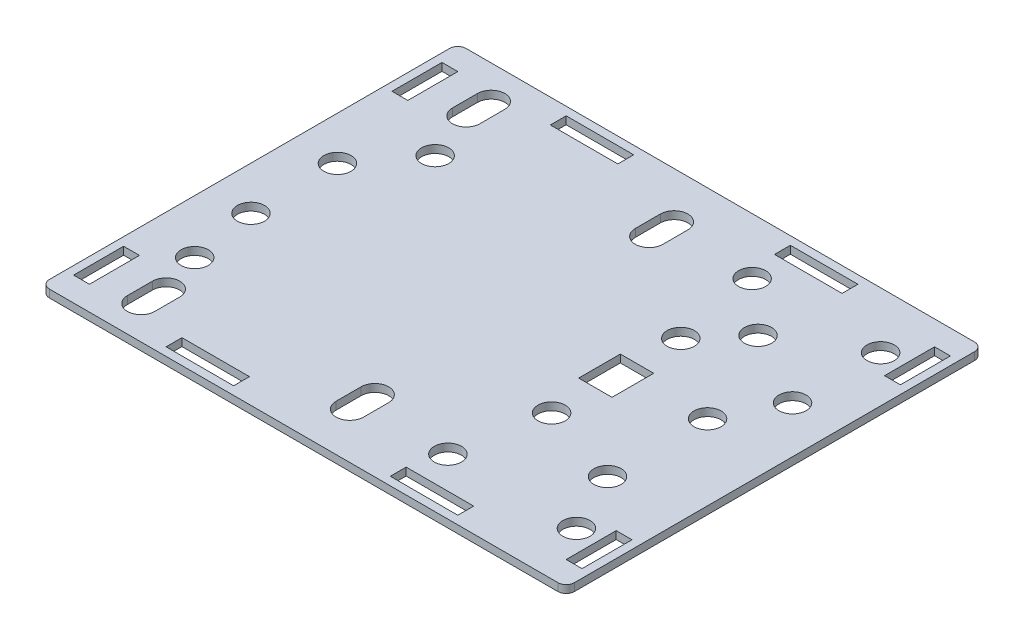
SolidWorks part; units mm, degrees
material "PE High Density Film"
ref_plane "Front Plane" through (0, 0, 0) normal (0, 0, 1) x (1, 0, 0)
ref_plane "Top Plane" through (0, 0, 0) normal (0, 1, 0) x (1, 0, 0)
ref_plane "Right Plane" through (0, 0, 0) normal (1, 0, 0) x (0, 0, -1)
sketch "Sketch1" plane through (0, 0, 0) normal (0, 1, 0) x (1, 0, 0)
  line L1 (-76.2, 63.5) -> (76.2, 63.5)
  line L2 (-76.2, 63.5) -> (-76.2, -63.5)
  line L3 (-76.2, -63.5) -> (76.2, -63.5)
  line L4 (76.2, 63.5) -> (76.2, -63.5)
  line L5 (-76.2, 63.5) -> (76.2, -63.5) construction
  line L6 (-76.2, -63.5) -> (76.2, 63.5) construction
  point P0 (0, 0)
  dimension "D1" = 127
  dimension "D2" = 152.4
extrude "Boss-Extrude1" add sketch "Sketch1" along normal blind 2.3622
sketch "Sketch9" plane through (0, 0, 0) normal (0, -1, 0) x (1, 0, 0)
  circle A0 centre (60.8584, 27.94) radius 4.15
  circle A1 centre (60.8584, -2.54) radius 4.15
  dimension "D1" = 8.3
  dimension "D2" = 8.3
extrude "Cut-Extrude8" cut sketch "Sketch9" against normal through all
sketch "Sketch16" plane through (0, 0, 0) normal (0, -1, 0) x (-1, 0, 0)
  circle A0 centre (-69.5999, 19.7043) radius 4.15
  circle A1 centre (-46.5226, 32.2642) radius 4.15
  dimension "D1" = 8.3
extrude "Cut-Extrude14" cut sketch "Sketch16" against normal through all
sketch "Sketch26" plane through (0, 2.3622, 0) normal (0, 1, 0) x (1, 0, 0)
  line L1 (40.64, 6.35) -> (30.48, 6.35)
  line L2 (40.64, 6.35) -> (40.64, -6.35)
  line L3 (40.64, -6.35) -> (30.48, -6.35)
  line L4 (30.48, 6.35) -> (30.48, -6.35)
extrude "Cut-Extrude26" cut sketch "Sketch26" against normal through all
sketch "Sketch27" plane through (0, 0, 0) normal (0, -1, 0) x (1, 0, 0)
  circle A0 centre (-59.8314, 33.0604) radius 4.15
  circle A1 centre (-50.0917, -30.48) radius 4.15
  dimension "D1" = 8.3
extrude "Cut-Extrude27" cut sketch "Sketch27" against normal through all
sketch "Sketch29" plane through (0, 2.3622, 0) normal (0, 1, 0) x (1, 0, 0)
  circle A0 centre (35.56, 19.6812) radius 4.15
  circle A1 centre (35.56, -19.6812) radius 4.15
  dimension "D1" = 8.3
extrude "Cut-Extrude28" cut sketch "Sketch29" against normal through all
sketch "Sketch30" plane through (0, 2.3622, 0) normal (0, 1, 0) x (1, 0, 0)
  line L0 (75.66, -63.5) -> (-73.66, -63.5) construction
  line L2 (-76.2, -63.5) -> (76.2, -63.5) construction
  circle A0 centre (69.8033, -46.355) radius 4.15
  circle A1 centre (30.6352, -46.355) radius 4.15
  dimension "D1" = 8.3
  dimension "D2" = 17.145
  dimension "D3" = 17.145
extrude "Cut-Extrude29" cut sketch "Sketch30" against normal through all
mirror "Mirror8" about plane through (0, 0, 0) normal (0, 0, 1) of "Cut-Extrude29"
sketch "Sketch31" plane through (0, 2.3622, 0) normal (0, 1, 0) x (1, 0, 0)
  circle A0 centre (-62.9423, -12.7955) radius 4.15
  circle A1 centre (-62.9423, 13.5496) radius 4.15
  dimension "D1" = 8.3
extrude "Cut-Extrude30" cut sketch "Sketch31" against normal through all
sketch "Sketch32" plane through (0, 2.3622, 0) normal (0, 1, 0) x (1, 0, 0)
  line L0 (76.2, -46.4055) -> (73.953, -46.4055) construction
  line L1 (76.2, -63.5) -> (76.2, 63.5) construction
  circle A0 centre (69.8033, -46.355) radius 4.15 construction
sketch "Sketch34" plane through (76.2, 0, 0) normal (1, 0, 0) x (0, 0, -1)
  line L1 (-63.5, 2.3622) -> (63.5, 2.3622)
  line L2 (-63.5, 2.3622) -> (-63.5, 0)
  line L3 (-63.5, 0) -> (63.5, 0)
  line L4 (63.5, 2.3622) -> (63.5, 0)
extrude "Boss-Extrude2" add sketch "Sketch34" along normal blind 7.62
sketch "Sketch36" plane through (0, 2.3622, 0) normal (0, 1, 0) x (1, 0, 0)
  line L0 (3.81, 63.5) -> (3.81, -76.7285) construction
  line L1 (83.82, 63.5) -> (-76.2, 63.5) construction
sketch "Sketch37" plane through (0, 0, 0) normal (0, -1, 0) x (-1, 0, 0)
  line L0 (-3.81, -63.5) -> (-3.81, 68.2955) construction
  line L1 (76.2, -63.5) -> (-83.82, -63.5) construction
ref_plane "Plane1" through (3.81, 0, 0) normal (1, 0, 0) x (0, 0, -1)
sketch "Sketch38" plane through (0, 2.3622, 0) normal (0, 1, 0) x (1, 0, 0)
  line L0 (3.81, 63.5) -> (3.81, -76.7285) construction
  line L1 (48.26, -60.96) -> (-40.64, -60.96)
  line L2 (48.26, -60.96) -> (48.26, -56.134)
  line L3 (48.26, -56.134) -> (-40.64, -56.134)
  line L4 (-40.64, -60.96) -> (-40.64, -56.134)
  line L5 (48.26, -60.96) -> (-40.64, -56.134) construction
  line L6 (48.26, -56.134) -> (-40.64, -60.96) construction
  line L7 (-76.2, -63.5) -> (83.82, -63.5) construction
  point P0 (3.81, -58.547)
  dimension "D1" = 2.54
  dimension "D2" = 4.826
  dimension "D3" = 88.9
extrude "Cut-Extrude34" cut sketch "Sketch38" against normal blind 7.62
mirror "Mirror13" about plane through (0, 0, 0) normal (0, 0, 1) of "Cut-Extrude34"
sketch "Sketch39" plane through (0, 2.3622, 0) normal (0, 1, 0) x (1, 0, 0)
  line L0 (83.82, 63.5) -> (83.82, -63.5) construction
  line L1 (81.28, -56.134) -> (76.454, -56.134)
  line L2 (81.28, -56.134) -> (81.28, -40.894)
  line L3 (81.28, -40.894) -> (76.454, -40.894)
  line L4 (76.454, -56.134) -> (76.454, -40.894)
  line L5 (81.28, -56.134) -> (76.454, -40.894) construction
  line L6 (81.28, -40.894) -> (76.454, -56.134) construction
  line L7 (48.26, -56.134) -> (-40.64, -56.134) construction
  point P0 (78.867, -48.514)
  dimension "D1" = 4.826
  dimension "D2" = 2.54
  dimension "D3" = 15.24
  dimension "D4" = 0
extrude "Cut-Extrude35" cut sketch "Sketch39" against normal blind 7.62
mirror "Mirror14" about plane through (0, 0, 0) normal (0, 0, 1) of "Cut-Extrude35"
mirror "Mirror15" about plane through (3.81, 0, 0) normal (1, 0, 0) of "Mirror14", "Cut-Extrude35"
sketch "Sketch13" plane through (0, 0, 0) normal (0, -1, 0) x (-1, 0, 0)
  line L0 (55.88, -45.72) -> (55.88, -53.34) construction
  line L1 (60.0529, -45.72) -> (60.0529, -53.34)
  line L2 (51.7071, -45.72) -> (51.7071, -53.34)
  line L3 (76.2, -63.5) -> (-83.82, -63.5) construction
  line L4 (76.2, 61.0698) -> (76.2, -60.8502) construction
  line L5 (-3.81, 49.403) -> (-3.81, 41.783) construction
  line L6 (0.381, 49.403) -> (0.381, 41.783)
  line L7 (-8.001, 49.403) -> (-8.001, 41.783)
  line L8 (-3.81, 63.5) -> (-3.81, -76.7285) construction
  line L10 (-48.26, 56.134) -> (40.64, 56.134) construction
  arc A0 (60.0529, -45.72) -> (51.7071, -45.72) centre (55.88, -45.72) ccw
  arc A1 (51.7071, -53.34) -> (60.0529, -53.34) centre (55.88, -53.34) ccw
  arc A2 (0.381, 49.403) -> (-8.001, 49.403) centre (-3.81, 49.403) ccw
  arc A3 (-8.001, 41.783) -> (0.381, 41.783) centre (-3.81, 41.783) ccw
  point P2 (55.88, -49.53)
  point P13 (-3.81, 45.593)
  point P28 (-3.81, 53.594)
  dimension "D5" = 2.54
  dimension "D1" = 7.62
  dimension "D2" = 10.16
  dimension "D3" = 20.32
  dimension "D4" = 7.62
  dimension "D6" = 8.382
extrude "Cut-Extrude12" cut sketch "Sketch13" against normal through all
mirror "Mirror16" about plane through (0, 0, 0) normal (0, 0, 1) of "Cut-Extrude12"
sketch "Sketch40" plane through (0, 0, 60.96) normal (0, 0, -1) x (-1, 0, 0)
  line L0 (40.64, 0) -> (-48.26, 0) construction
  line L1 (20.066, 0) -> (-27.686, 0)
  line L2 (20.066, 0) -> (20.066, 2.3622)
  line L3 (20.066, 2.3622) -> (-27.686, 2.3622)
  line L4 (-27.686, 0) -> (-27.686, 2.3622)
  line L5 (40.64, 2.3622) -> (-48.26, 2.3622) construction
  line L6 (40.64, 0) -> (40.64, 2.3622) construction
  line L7 (-48.26, 0) -> (-48.26, 2.3622) construction
  dimension "D1" = 20.574
  dimension "D2" = 20.574
extrude "Boss-Extrude3" add sketch "Sketch40" along normal up to vertex (4.826 mm away)
mirror "Mirror17" about plane through (0, 0, 0) normal (0, 0, 1) of "Boss-Extrude3"
fillet "Fillet2" radius 2.54 4 edges at (83.82, 1.1811, 63.5) (83.82, 1.1811, -63.5) (-76.2, 1.1811, -63.5) (-76.2, 1.1811, 63.5)
